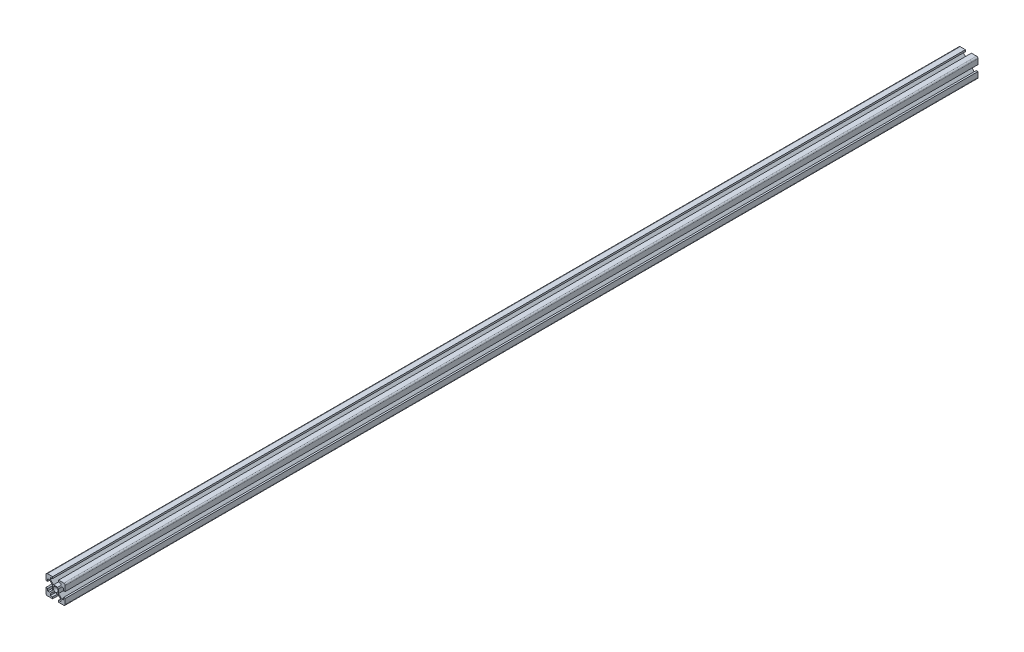
SolidWorks part; units mm, degrees
ref_plane "前视基准面" through (0, 0, 0) normal (0, 0, 1) x (1, 0, 0)
ref_plane "上视基准面" through (0, 0, 0) normal (0, 1, 0) x (1, 0, 0)
ref_plane "右视基准面" through (0, 0, 0) normal (1, 0, 0) x (0, 0, -1)
sketch "草图1" plane through (0, 0, 0) normal (0, 0, 1) x (1, 0, 0)
  line L0 (-10, -3.1) -> (-8.2, -3.1)
  line L1 (-8.5, 10) -> (8.5, 10)
  line L2 (-10, 8.5) -> (-10, -8.5)
  line L3 (-8.5, -10) -> (8.5, -10)
  line L4 (10, 8.5) -> (10, -8.5)
  line L5 (-10, 10) -> (10, -10) construction
  line L6 (-10, -10) -> (10, 10) construction
  line L7 (-3.0541, 3.1) -> (3.0541, 3.1)
  line L8 (-3.0541, 3.1) -> (-3.0541, -3.1)
  line L9 (-3.0541, -3.1) -> (3.0541, -3.1)
  line L10 (3.0541, 3.1) -> (3.0541, -3.1)
  line L11 (-3.0541, 3.1) -> (3.0541, -3.1) construction
  line L12 (-3.0541, -3.1) -> (3.0541, 3.1) construction
  line L13 (-8.2, -3.1) -> (-8.2, -5.5)
  line L14 (-8.2, -5.5) -> (-6.3971, -5.5)
  line L15 (-6.3971, -5.5) -> (-3.0541, -2.1571)
  line L16 (-5.5, 6.3971) -> (-2.1571, 3.0541)
  line L17 (-5.5, 8.2) -> (-5.5, 6.3971)
  line L18 (-3.1, 8.2) -> (-5.5, 8.2)
  line L19 (-3.1, 10) -> (-3.1, 8.2)
  line L20 (6.3971, 5.5) -> (3.0541, 2.1571)
  line L21 (8.2, 5.5) -> (6.3971, 5.5)
  line L22 (8.2, 3.1) -> (8.2, 5.5)
  line L23 (10, 3.1) -> (8.2, 3.1)
  line L24 (5.5, -6.3971) -> (2.1571, -3.0541)
  line L25 (5.5, -8.2) -> (5.5, -6.3971)
  line L26 (3.1, -8.2) -> (5.5, -8.2)
  line L27 (3.1, -10) -> (3.1, -8.2)
  line L28 (-3.1, -10) -> (-3.1, -8.2)
  line L29 (-3.1, -8.2) -> (-5.5, -8.2)
  line L30 (-5.5, -8.2) -> (-5.5, -6.3971)
  line L31 (-5.5, -6.3971) -> (-2.1571, -3.0541)
  line L32 (-8.2, 5.5) -> (-6.3971, 5.5)
  line L33 (-6.3971, 5.5) -> (-3.0541, 2.1571)
  line L34 (-8.2, 3.1) -> (-8.2, 5.5)
  line L35 (-10, 3.1) -> (-8.2, 3.1)
  line L36 (5.5, 8.2) -> (5.5, 6.3971)
  line L37 (5.5, 6.3971) -> (2.1571, 3.0541)
  line L38 (3.1, 8.2) -> (5.5, 8.2)
  line L39 (3.1, 10) -> (3.1, 8.2)
  line L40 (8.2, -5.5) -> (6.3971, -5.5)
  line L41 (6.3971, -5.5) -> (3.0541, -2.1571)
  line L42 (8.2, -3.1) -> (8.2, -5.5)
  line L43 (10, -3.1) -> (8.2, -3.1)
  circle A0 centre (0, 0) radius 2.5
  arc A1 (-10, 8.5) -> (-8.5, 10) centre (-8.5, 8.5) cw
  arc A2 (-10, -8.5) -> (-8.5, -10) centre (-8.5, -8.5) ccw
  arc A3 (8.5, 10) -> (10, 8.5) centre (8.5, 8.5) cw
  arc A4 (10, -8.5) -> (8.5, -10) centre (8.5, -8.5) cw
  point P0 (0, 0)
  point P20 (0, 0)
  point P26 (0, 0)
  point P32 (0, 0)
  point P38 (0, 0)
  point P60 (0, 0)
  dimension "D1" = 4
  dimension "D3" = 1.5
  dimension "D4" = 1.5
  dimension "D5" = 1.5
  dimension "D2" = 4
extrude "凸台-拉伸1" add sketch "草图1" along normal blind 950
sketch "草图2" plane through (0, 0, 950) normal (0, 0, 1) x (1, 0, 0)
  line L1 (48.9007, 39.2379) -> (-13.6703, 39.2379)
  line L2 (48.9007, 39.2379) -> (48.9007, -16.2916)
  line L3 (48.9007, -16.2916) -> (-13.6703, -16.2916)
  line L4 (-13.6703, 39.2379) -> (-13.6703, -16.2916)
  line L5 (48.9007, 39.2379) -> (-13.6703, -16.2916) construction
  line L6 (48.9007, -16.2916) -> (-13.6703, 39.2379) construction
  point P0 (17.6152, 11.4732)
sketch "草图3" plane through (0, 0, 950) normal (0, 0, 1) x (1, 0, 0)
  line L1 (57.7363, -43.4272) -> (-16.4394, -43.4272)
  line L2 (57.7363, -43.4272) -> (57.7363, 17.7693)
  line L3 (57.7363, 17.7693) -> (-16.4394, 17.7693)
  line L4 (-16.4394, -43.4272) -> (-16.4394, 17.7693)
  line L5 (57.7363, -43.4272) -> (-16.4394, 17.7693) construction
  line L6 (57.7363, 17.7693) -> (-16.4394, -43.4272) construction
  point P0 (20.6484, -12.8289)
sketch "草图4" plane through (0, 0, 0) normal (0, 0, -1) x (-1, 0, 0)
  line L1 (40.6178, -51.9283) -> (-12.1095, -51.9283)
  line L2 (40.6178, -51.9283) -> (40.6178, 15.6102)
  line L3 (40.6178, 15.6102) -> (-12.1095, 15.6102)
  line L4 (-12.1095, -51.9283) -> (-12.1095, 15.6102)
  line L5 (40.6178, -51.9283) -> (-12.1095, 15.6102) construction
  line L6 (40.6178, 15.6102) -> (-12.1095, -51.9283) construction
  point P0 (14.2541, -18.159)
sketch "草图5" plane through (0, 0, 0) normal (0, 0, -1) x (-1, 0, 0)
  line L1 (9.5607, -9.5607) -> (-9.5607, -9.5607)
  line L2 (9.5607, -9.5607) -> (9.5607, 9.5607)
  line L3 (9.5607, 9.5607) -> (-9.5607, 9.5607)
  line L4 (-9.5607, -9.5607) -> (-9.5607, 9.5607)
  line L5 (9.5607, -9.5607) -> (-9.5607, 9.5607) construction
  line L6 (9.5607, 9.5607) -> (-9.5607, -9.5607) construction
  arc A0 (-8.5, 10) -> (-10, 8.5) centre (-8.5, 8.5) ccw construction
  point P0 (0, 0)
sketch "草图6" plane through (0, 0, 0) normal (0, 0, -1) x (-1, 0, 0)
  line L1 (9.5607, -9.5607) -> (-9.5607, -9.5607)
  line L2 (9.5607, -9.5607) -> (9.5607, 9.5607)
  line L3 (9.5607, 9.5607) -> (-9.5607, 9.5607)
  line L4 (-9.5607, -9.5607) -> (-9.5607, 9.5607)
  line L5 (9.5607, -9.5607) -> (-9.5607, 9.5607) construction
  line L6 (9.5607, 9.5607) -> (-9.5607, -9.5607) construction
  arc A0 (-8.5, 10) -> (-10, 8.5) centre (-8.5, 8.5) ccw construction
  point P0 (0, 0)
sketch "草图7" plane through (0, 0, 0) normal (0, 0, -1) x (-1, 0, 0)
  line L1 (9.5607, -9.5607) -> (-9.5607, -9.5607)
  line L2 (9.5607, -9.5607) -> (9.5607, 9.5607)
  line L3 (9.5607, 9.5607) -> (-9.5607, 9.5607)
  line L4 (-9.5607, -9.5607) -> (-9.5607, 9.5607)
  line L5 (9.5607, -9.5607) -> (-9.5607, 9.5607) construction
  line L6 (9.5607, 9.5607) -> (-9.5607, -9.5607) construction
  arc A0 (-8.5, 10) -> (-10, 8.5) centre (-8.5, 8.5) ccw construction
  point P0 (0, 0)
